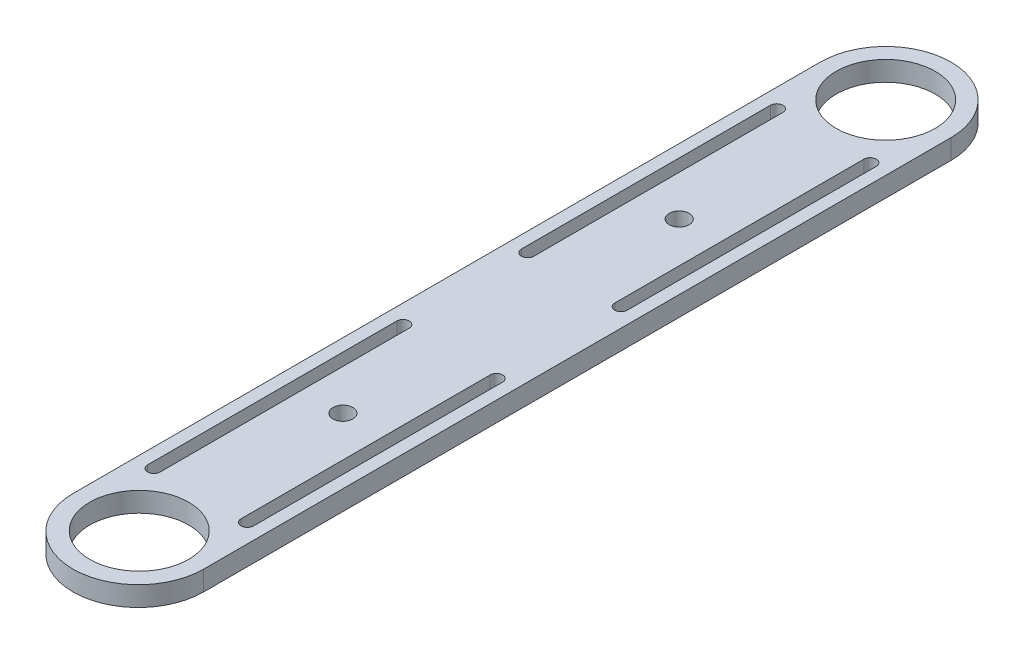
SolidWorks part; units mm, degrees
ref_plane "Front Plane" through (0, 0, 0) normal (0, 0, 1) x (1, 0, 0)
ref_plane "Top Plane" through (0, 0, 0) normal (0, 1, 0) x (1, 0, 0)
ref_plane "Right Plane" through (0, 0, 0) normal (1, 0, 0) x (0, 0, -1)
sketch "Sketch1" plane through (0, 0, 0) normal (0, 1, 0) x (1, 0, 0)
  line L0 (-10.5, 0) -> (-10.5, -120)
  line L1 (10.5, 0) -> (10.5, -120)
  arc A0 (10.5, 0) -> (-10.5, 0) centre (0, 0) ccw
  arc A1 (-10.5, -120) -> (10.5, -120) centre (0, -120) ccw
  dimension "D1" = 10.5
  dimension "D2" = 120
extrude "Boss-Extrude1" add sketch "Sketch1" along normal blind 3.175
sketch "Sketch3" plane through (0, 0, 0) normal (0, -1, 0) x (1, 0, 0)
  line L0 (-8.5, 110) -> (-8.5, 70) construction
  line L1 (-6.5, 70) -> (-6.5, 110) construction
  line L2 (6.5, 110) -> (6.5, 70) construction
  line L3 (8.5, 70) -> (8.5, 110) construction
  line L4 (8.5, 10) -> (8.5, 50) construction
  line L5 (6.5, 50) -> (6.5, 10) construction
  line L6 (-8.5, 50) -> (-8.5, 10) construction
  line L7 (-6.5, 10) -> (-6.5, 50) construction
  line L8 (-8.5, 110) -> (-8.5, 70)
  line L9 (-6.5, 70) -> (-6.5, 110)
  line L10 (6.5, 110) -> (6.5, 70)
  line L11 (8.5, 70) -> (8.5, 110)
  line L12 (8.5, 10) -> (8.5, 50)
  line L13 (6.5, 50) -> (6.5, 10)
  line L14 (-8.5, 50) -> (-8.5, 10)
  line L15 (-6.5, 10) -> (-6.5, 50)
  arc A1 (-8.5, 70) -> (-6.5, 70) centre (-7.5, 70) ccw construction
  arc A2 (8.5, 110) -> (6.5, 110) centre (7.5, 110) ccw construction
  arc A3 (6.5, 70) -> (8.5, 70) centre (7.5, 70) ccw construction
  arc A4 (6.5, 10) -> (8.5, 10) centre (7.5, 10) ccw construction
  arc A5 (8.5, 50) -> (6.5, 50) centre (7.5, 50) ccw construction
  arc A6 (-6.5, 50) -> (-8.5, 50) centre (-7.5, 50) ccw construction
  arc A7 (-8.5, 10) -> (-6.5, 10) centre (-7.5, 10) ccw construction
  arc A8 (-8.5, 70) -> (-6.5, 70) centre (-7.5, 70) ccw
  arc A9 (8.5, 110) -> (6.5, 110) centre (7.5, 110) ccw
  arc A10 (6.5, 70) -> (8.5, 70) centre (7.5, 70) ccw
  arc A11 (6.5, 10) -> (8.5, 10) centre (7.5, 10) ccw
  arc A12 (8.5, 50) -> (6.5, 50) centre (7.5, 50) ccw
  arc A13 (-6.5, 50) -> (-8.5, 50) centre (-7.5, 50) ccw
  arc A14 (-8.5, 10) -> (-6.5, 10) centre (-7.5, 10) ccw
  arc A15 (-6.5, 110) -> (-8.5, 110) centre (-7.5, 110) ccw construction
  arc A16 (-6.5, 110) -> (-8.5, 110) centre (-7.5, 110) ccw
extrude "Cut-Extrude2" cut sketch "Sketch3" against normal through all both and the other way through all
sketch "Sketch4" plane through (0, 3.175, 0) normal (0, 1, 0) x (1, 0, 0)
  circle A0 centre (0, -33.15) radius 1.6 construction
  circle A1 centre (0, -87.15) radius 1.6 construction
  circle A2 centre (0, -33.15) radius 1.6
  circle A3 centre (0, -87.15) radius 1.6
extrude "Cut-Extrude3" cut sketch "Sketch4" against normal through all both and the other way through all
sketch "Sketch5" plane through (0, 3.175, 0) normal (0, 1, 0) x (1, 0, 0)
  circle A0 centre (0, 0) radius 7.95 construction
  circle A1 centre (-0.0032, -119.85) radius 7.95 construction
  circle A2 centre (0, 0) radius 7.95
  circle A3 centre (-0.0032, -119.85) radius 7.95
extrude "Cut-Extrude4" cut sketch "Sketch5" against normal through all both and the other way through all
